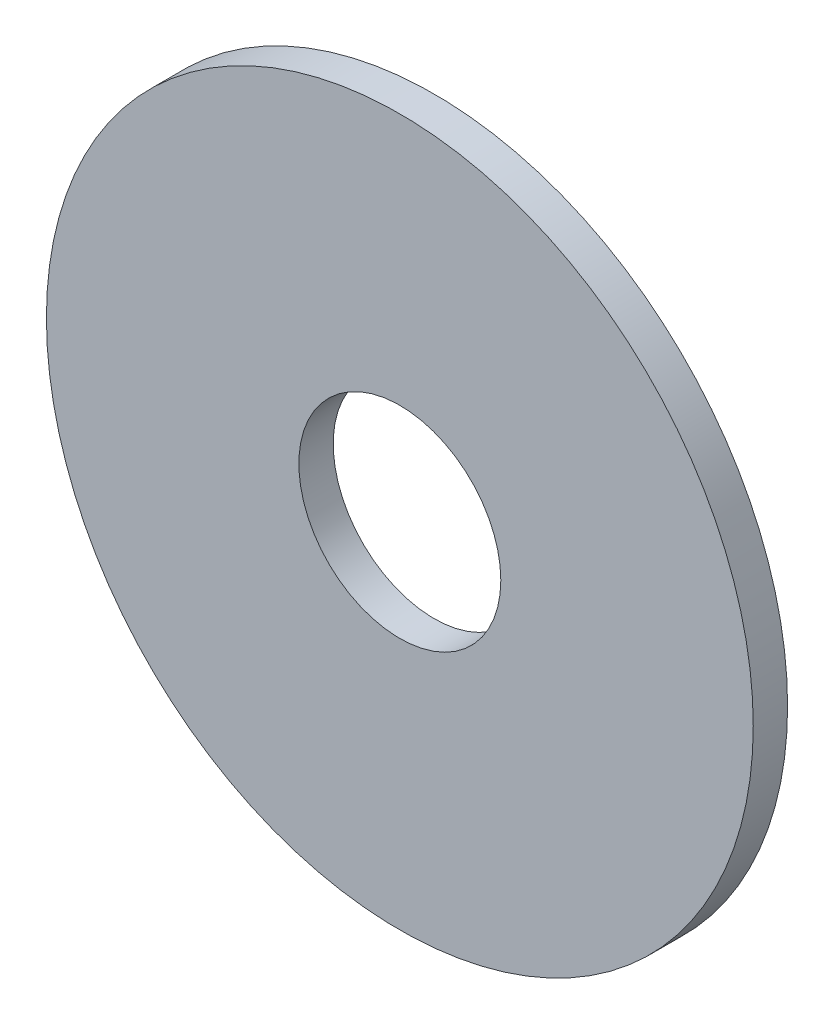
SolidWorks part; units mm, degrees
material "ABS PC"
ref_plane "Front Plane" through (0, 0, 0) normal (0, 0, 1) x (1, 0, 0)
ref_plane "Top Plane" through (0, 0, 0) normal (0, 1, 0) x (1, 0, 0)
ref_plane "Right Plane" through (0, 0, 0) normal (1, 0, 0) x (0, 0, -1)
sketch "Sketch1" plane through (0, 0, 0) normal (0, 0, 1) x (1, 0, 0)
  circle A0 centre (0, 0) radius 17.5
  circle A1 centre (0, 0) radius 5
  dimension "D1" = 35
  dimension "D2" = 10
extrude "Boss-Extrude1" add sketch "Sketch1" along normal blind 1.7
equation "\"smallPulleyTeeth\"= 15"
equation "\"largePulleyTeeth\"= 30"
equation "\"eighthThick\"= 2.9mm"
equation "\"sixteenthThick\" = 1.7mm"
equation "\"wheelEighthThick\"=3.0mm"
equation "\"quarterThick\"=5.6mm"
equation "\"bushingDiam\"= 7.85mm"
equation "\"plateBoltCircle\"= 65mm"
equation "\"plateBoltDiam\"= 5mm"
equation "\"D1@Boss-Extrude1\"=\"sixteenthThick\""
